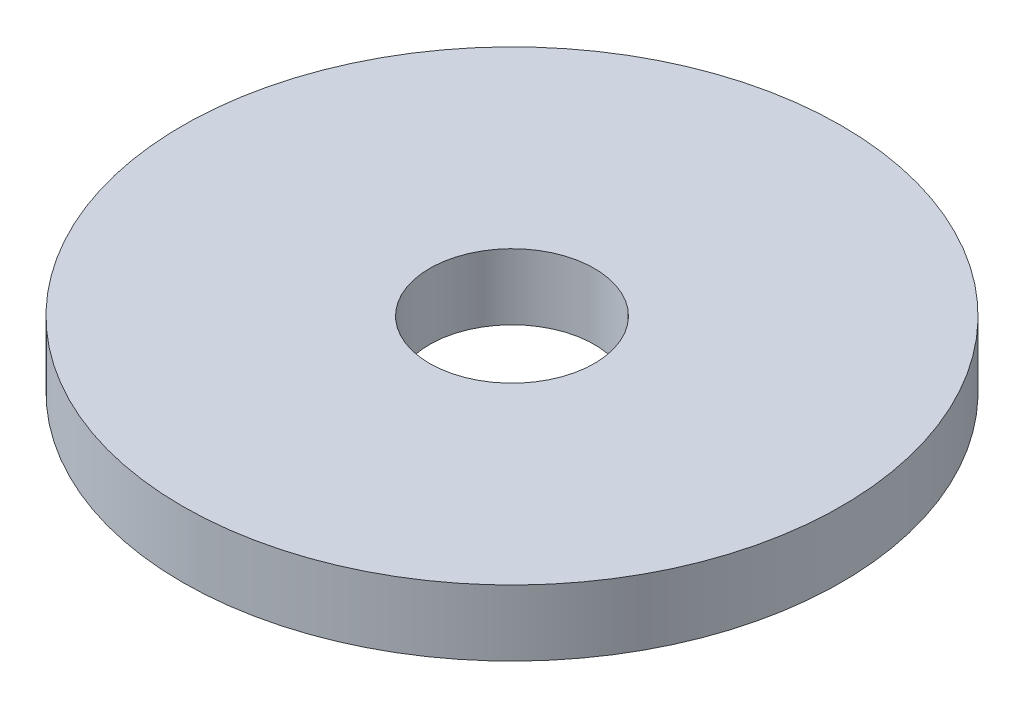
SolidWorks part; units mm, degrees
ref_plane "Front Plane" through (0, 0, 0) normal (0, 0, 1) x (1, 0, 0)
ref_plane "Top Plane" through (0, 0, 0) normal (0, 1, 0) x (1, 0, 0)
ref_plane "Right Plane" through (0, 0, 0) normal (1, 0, 0) x (0, 0, -1)
sketch "Sketch1" plane through (0, 0, 0) normal (0, 1, 0) x (1, 0, 0)
  circle A0 centre (0, 0) radius 2.125
  circle A1 centre (0, 0) radius 12.5
extrude "Boss-Extrude1" add sketch "Sketch1" along normal blind 2
sketch "Sketch2" plane through (0, 2, 0) normal (0, 1, 0) x (1, 0, 0)
  circle A0 centre (0, 0) radius 2.5
extrude "Cut-Extrude1" cut sketch "Sketch2" against normal blind 10
sketch "Sketch3" plane through (0, 2, 0) normal (0, 1, 0) x (1, 0, 0)
  circle A0 centre (0, 0) radius 12.5
  circle A1 centre (0, 0) radius 10
extrude "Cut-Extrude2" cut sketch "Sketch3" against normal blind 10
